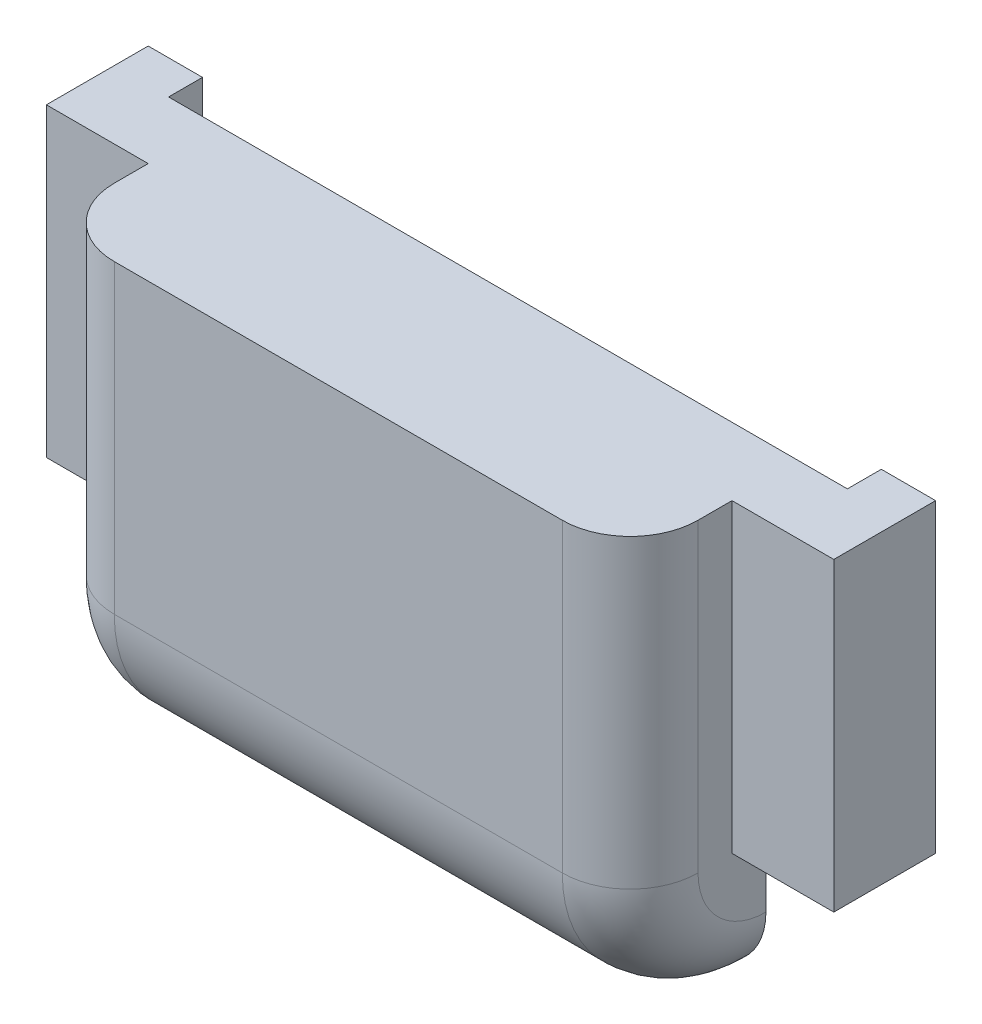
SolidWorks part; units mm, degrees
ref_plane "前视基准面" through (0, 0, 0) normal (0, 0, 1) x (1, 0, 0)
ref_plane "上视基准面" through (0, 0, 0) normal (0, 1, 0) x (1, 0, 0)
ref_plane "右视基准面" through (0, 0, 0) normal (1, 0, 0) x (0, 0, -1)
sketch "草图1" plane through (0, 0, 0) normal (0, 0, 1) x (1, 0, 0)
  line L1 (-4.3, 3.25) -> (4.3, 3.25)
  line L2 (-4.3, 3.25) -> (-4.3, -3.25)
  line L3 (-4.3, -3.25) -> (4.3, -3.25)
  line L4 (4.3, 3.25) -> (4.3, -3.25)
  line L5 (-4.3, 3.25) -> (4.3, -3.25) construction
  line L6 (-4.3, -3.25) -> (4.3, 3.25) construction
  point P0 (0, 0)
  dimension "D1" = 8.6
  dimension "D2" = 6.5
extrude "凸台-拉伸1" add sketch "草图1" along normal blind 3
fillet "圆角1" radius 2 1 edges at (0, -3.25, 3)
sketch "草图2" plane through (4.3, 0, 0) normal (1, 0, 0) x (0, 0, -1)
  line L0 (0, -3.25) -> (0, 3.25) construction
  line L1 (0, -1.25) -> (-1.5, -1.25)
  line L2 (0, -1.25) -> (0, 3.25)
  line L3 (0, 3.25) -> (-1.5, 3.25)
  line L4 (-1.5, -1.25) -> (-1.5, 3.25)
  line L5 (-1, -3.25) -> (0, -3.25) construction
  dimension "D1" = 2
  dimension "D2" = 4.5
  dimension "D3" = 1.5
extrude "凸台-拉伸2" add sketch "草图2" along normal blind 1.5
sketch "草图3" plane through (-4.3, 0, 0) normal (-1, 0, 0) x (0, 0, 1)
  line L0 (0, 3.25) -> (0, -3.25) construction
  line L1 (0, 3.25) -> (1.5, 3.25)
  line L2 (0, 3.25) -> (0, -1.25)
  line L3 (0, -1.25) -> (1.5, -1.25)
  line L4 (1.5, 3.25) -> (1.5, -1.25)
  line L5 (1, -3.25) -> (0, -3.25) construction
  dimension "D1" = 1.5
  dimension "D2" = 2
  dimension "D3" = 4.5
extrude "凸台-拉伸3" add sketch "草图3" along normal blind 1.5
fillet "圆角2" radius 1 3 edges at (4.3, -3.25, 0.5) (4.3, -2.6642, 2.4142) (4.3, 1, 3)
fillet "圆角3" radius 1 3 edges at (-4.3, -3.25, 0.5) (-4.3, -2.6642, 2.4142) (-4.3, 1, 3)
sketch "草图4" plane through (0, 0, 0) normal (0, 0, -1) x (-1, 0, 0)
  line L0 (-4.3, -1.25) -> (-4.3, -2.25)
  line L1 (-3.3, -3.25) -> (3.3, -3.25)
  line L2 (4.3, -2.25) -> (4.3, -1.25)
  line L3 (4.3, -1.25) -> (-4.3, -1.25)
  arc A0 (-4.3, -2.25) -> (-3.3, -3.25) centre (-3.3, -2.25) ccw
  arc A1 (3.3, -3.25) -> (4.3, -2.25) centre (3.3, -2.25) ccw
extrude "切除-拉伸1" cut sketch "草图4" against normal blind 1
sketch "草图5" plane through (0, 0, 0) normal (0, 0, -1) x (-1, 0, 0)
  line L0 (-5.8, -1.25) -> (-5.8, 3.25) construction
  line L1 (-5, 3.25) -> (5, 3.25)
  line L2 (-5, 3.25) -> (-5, -1.25)
  line L3 (-5, -1.25) -> (5, -1.25)
  line L4 (5, 3.25) -> (5, -1.25)
  line L5 (5.8, 3.25) -> (5.8, -1.25) construction
  line L6 (4.3, -1.25) -> (-4.3, -1.25) construction
  line L7 (-5.8, 3.25) -> (5.8, 3.25) construction
  dimension "D1" = 0.8
  dimension "D2" = 0.8
  dimension "D3" = 0
  dimension "D4" = 0
extrude "切除-拉伸2" cut sketch "草图5" against normal blind 0.5
